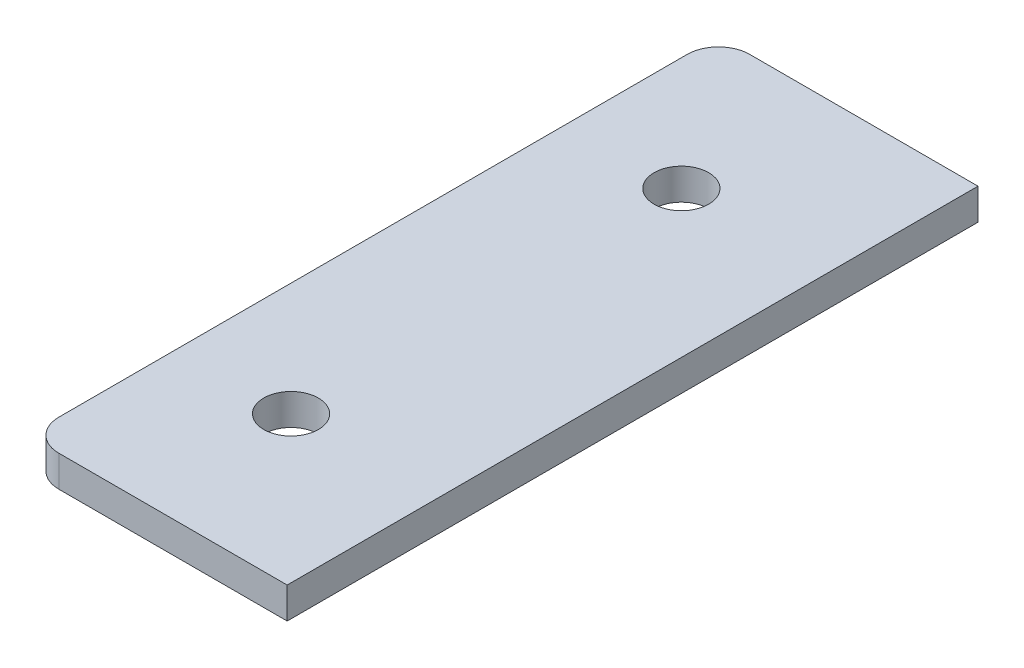
SolidWorks part; units mm, degrees
material "ASTM A36 Steel"
ref_plane "Front Plane" through (0, 0, 0) normal (0, 0, 1) x (1, 0, 0)
ref_plane "Top Plane" through (0, 0, 0) normal (0, 1, 0) x (1, 0, 0)
ref_plane "Right Plane" through (0, 0, 0) normal (1, 0, 0) x (0, 0, -1)
sketch "Sketch1" plane through (0, 0, 0) normal (0, 1, 0) x (1, 0, 0)
  line L0 (45.2324, 82.3216) -> (45.2324, -94.6784)
  line L1 (45.2324, 82.3216) -> (-13.2676, 82.3216)
  line L2 (-21.2676, 74.3216) -> (-21.2676, -86.6784)
  line L3 (-13.2676, -94.6784) -> (45.2324, -94.6784)
  arc A0 (-13.2676, 82.3216) -> (-21.2676, 74.3216) centre (-13.2676, 74.3216) ccw
  arc A1 (-21.2676, -86.6784) -> (-13.2676, -94.6784) centre (-13.2676, -86.6784) ccw
  circle A3 centre (7.7324, -56.1784) radius 7
  circle A4 centre (7.7324, 43.8216) radius 7
  point P12 (45.2324, -6.1784)
  dimension "D1" = 66.5
  dimension "D3" = 14
  dimension "D4" = 14
  dimension "D5" = 100
  dimension "D6" = 50
  dimension "D7" = 37.5
  dimension "D2" = 177
extrude "Boss-Extrude1" add sketch "Sketch1" along normal blind 8
